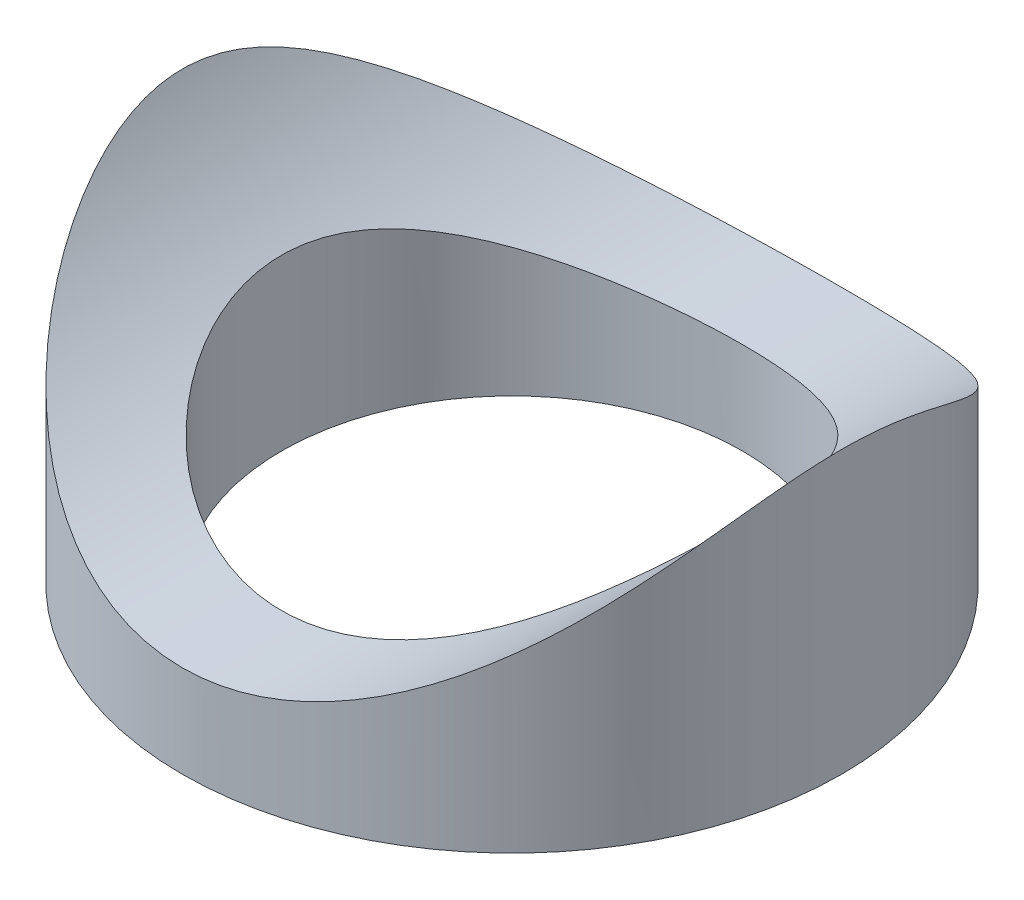
SolidWorks part; units mm, degrees
material "PTFE (general)"
ref_plane "Front Plane" through (0, 0, 0) normal (0, 0, 1) x (1, 0, 0)
ref_plane "Top Plane" through (0, 0, 0) normal (0, 1, 0) x (1, 0, 0)
ref_plane "Right Plane" through (0, 0, 0) normal (1, 0, 0) x (0, 0, -1)
sketch "Sketch1" plane through (0, 0, 0) normal (0, 1, 0) x (1, 0, 0)
  circle A0 centre (0, 0) radius 7.15
  circle A1 centre (0, 0) radius 5
  dimension "D1" = 10
  dimension "D2" = 14.3
extrude "Boss-Extrude1" add sketch "Sketch1" along normal blind 10
sketch "Sketch2" plane through (0, 0, 0) normal (0, 0, 1) x (1, 0, 0)
  line L0 (0, -5.5) -> (0, 5.5) construction
  circle A0 centre (0, 9.28) radius 8.28
  dimension "D2" = 16.56
  dimension "D3" = 9.28
  dimension "D1" = 0
extrude "Cut-Extrude1" cut sketch "Sketch2" against normal through all both and the other way through all
sketch "Sketch3" plane through (0, 0, 0) normal (0, -1, 0) x (1, 0, 0)
  circle A0 centre (0, 0) radius 7.15
  circle A1 centre (0, 0) radius 5
  circle A2 centre (0, 0) radius 7.15 construction
  dimension "D1" = 0
extrude "Boss-Extrude2" add sketch "Sketch3" along normal blind 1
